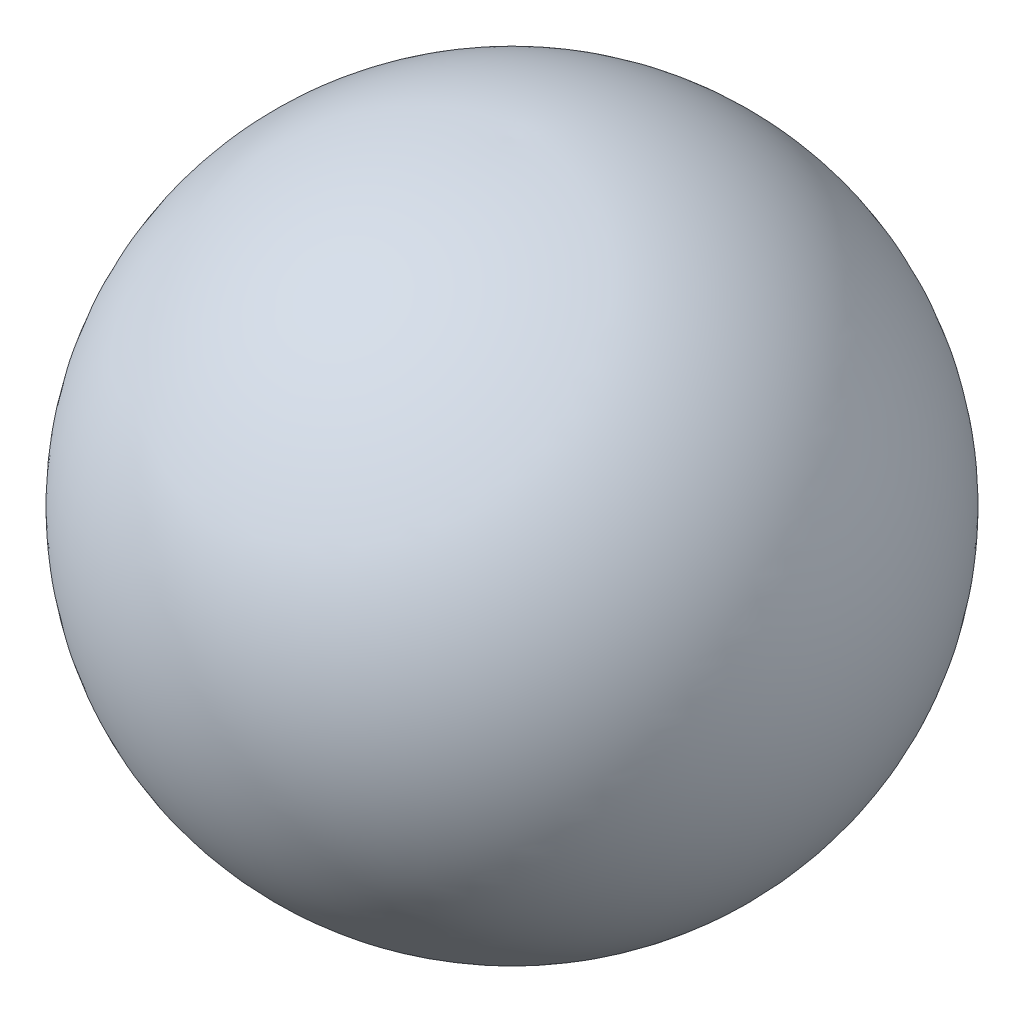
SolidWorks part; units mm, degrees
material "Alloy Steel"
ref_plane "Front Plane" through (0, 0, 0) normal (0, 0, 1) x (1, 0, 0)
ref_plane "Top Plane" through (0, 0, 0) normal (0, 1, 0) x (1, 0, 0)
ref_plane "Right Plane" through (0, 0, 0) normal (1, 0, 0) x (0, 0, -1)
sketch "Sketch1" plane through (0, 0, 0) normal (0, 0, 1) x (1, 0, 0)
  line L0 (0, 4.7625) -> (0, -4.7625)
  arc A0 (0, 4.7625) -> (0, -4.7625) centre (0.1513, 0) cw
  dimension "D1" = 9.525
  dimension "D2" = 4.7649
revolve "Revolve1" add sketch "Sketch1" angle 360 about L0
sketch "Sketch2" plane through (0, 0, 0) normal (0, 1, 0) x (1, 0, 0)
  circle A0 centre (0, 0) radius 4.9162 construction
  circle A1 centre (0, 0) radius 4.9162
